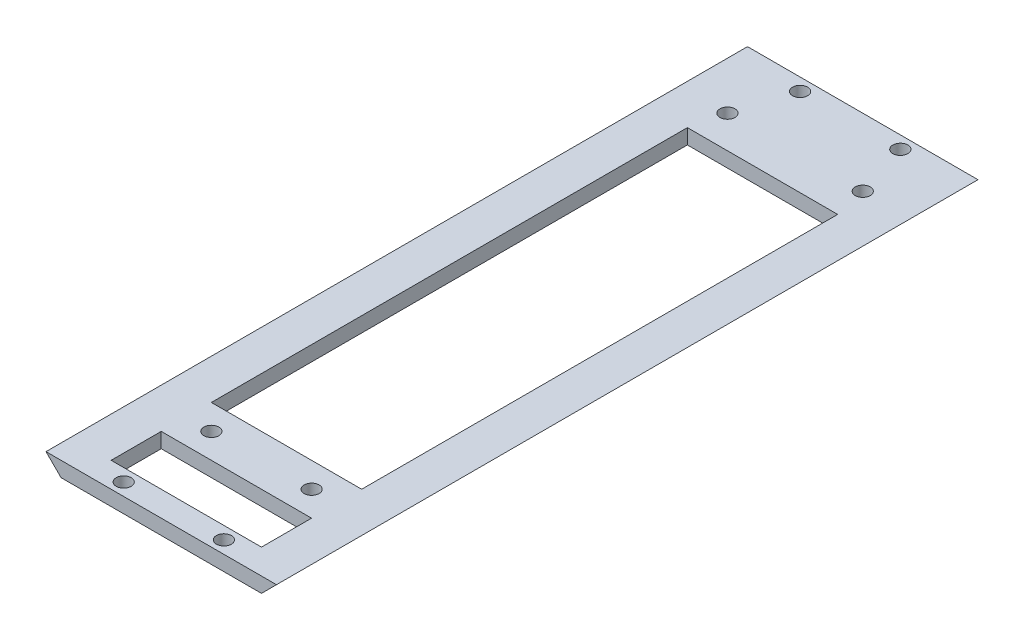
SolidWorks part; units mm, degrees
ref_plane "Front Plane" through (0, 0, 0) normal (0, 0, 1) x (1, 0, 0)
ref_plane "Top Plane" through (0, 0, 0) normal (0, 1, 0) x (1, 0, 0)
ref_plane "Right Plane" through (0, 0, 0) normal (1, 0, 0) x (0, 0, -1)
sketch "Sketch1" plane through (0, 0, 0) normal (0, 1, 0) x (1, 0, 0)
  line L1 (-25, -70) -> (25, -70)
  line L2 (-25, -70) -> (-25, 70)
  line L3 (-25, 70) -> (25, 70)
  line L4 (25, -70) -> (25, 70)
  line L5 (-25, -70) -> (25, 70) construction
  line L6 (-25, 70) -> (25, -70) construction
  point P0 (0, 0)
  dimension "D1" = 50
  dimension "D2" = 140
extrude "Boss-Extrude2" add sketch "Sketch1" along normal blind 5
sketch "Sketch2" plane through (0, 0, 70) normal (0, 0, 1) x (1, 0, 0)
  line L0 (-25, 0) -> (25, 0) construction
  line L5 (-25, 5) -> (-20, 0)
  line L7 (25, 5) -> (20, 0)
  line M2 (-25, 0) -> (25, 0)
  line M3 (25, 0) -> (25, 5)
  line M5 (-25, 5) -> (-25, 0)
extrude "Cut-Extrude1" cut sketch "Sketch2" against normal blind 152 contours L5 M5 M2 | L7 M3 M2
sketch "Sketch7" plane through (0, 0, -70) normal (0, 0, -1) x (-1, 0, 0)
  line L1 (-25, 5) -> (25, 5)
  line L2 (-25, 5) -> (-25, 3)
  line L3 (-25, 3) -> (25, 3)
  line L4 (25, 5) -> (25, 3)
  dimension "D1" = 2
extrude "Cut-Extrude5" cut sketch "Sketch7" against normal blind 197
sketch "Sketch8" plane through (0, 0, 0) normal (0, -1, 0) x (1, 0, 0)
  line L1 (-15, -65) -> (15, -65)
  line L2 (-15, -65) -> (-15, 65)
  line L3 (-15, 65) -> (15, 65)
  line L4 (15, -65) -> (15, 65)
  line L5 (-15, -65) -> (15, 65) construction
  line L6 (-15, 65) -> (15, -65) construction
  point P0 (0, 0)
  dimension "D1" = 30
  dimension "D2" = 130
extrude "Cut-Extrude6" cut sketch "Sketch8" against normal blind 197
sketch "Sketch9" plane through (0, 0, 0) normal (0, -1, 0) x (1, 0, 0)
  line L0 (20, 70) -> (20, -70) construction
  line L1 (-20, -70) -> (20, -70)
  line L2 (-20, -70) -> (-20, -50)
  line L3 (-20, -50) -> (20, -50)
  line L4 (20, -70) -> (20, -50)
  circle A0 centre (-13.5, -56.5) radius 1.5
  circle A1 centre (13.5, -56.5) radius 1.5
  dimension "D1" = 20
extrude "Boss-Extrude5" add sketch "Sketch9" against normal blind 3
sketch "Sketch10" plane through (0, 0, 0) normal (0, -1, 0) x (1, 0, 0)
  line L0 (15, -50) -> (15, 65) construction
  line L5 (-20, 70) -> (-20, -70) construction
  line L6 (-15, 55) -> (15, 55)
  line L7 (-15, 55) -> (-15, 45)
  line L8 (-15, 45) -> (15, 45)
  line L9 (15, 55) -> (15, 45)
  line L10 (-20, 55) -> (20, 55)
  line L11 (-20, 55) -> (-20, 45)
  line L12 (-20, 45) -> (20, 45)
  line L13 (20, 55) -> (20, 45)
  line L14 (20, 70) -> (20, -70) construction
  circle A0 centre (-10, 50) radius 1.5
  circle A1 centre (10, 50) radius 1.5
  line M16 (15, 65) -> (15, -50)
  line M18 (-15, -50) -> (-15, 65)
extrude "Boss-Extrude6" add sketch "Sketch10" against normal blind 3 contours L8 L6 A0 A1 M18 M16
sketch "Sketch11" plane through (0, 0, 0) normal (0, -1, 0) x (1, 0, 0)
  line L0 (-20, 0) -> (0, 0)
  line L4 (-20, 70) -> (-20, -70) construction
  circle A0 centre (-10, 67.5) radius 1.5
  circle A1 centre (10, 67.5) radius 1.5
  circle A2 centre (10, -67.5) radius 1.5
  circle A3 centre (-10, -67.5) radius 1.5
  point P15 (0, 0)
extrude "Cut-Extrude7" cut sketch "Sketch11" against normal blind 3 contours A3 | A2 | A1 | A0
